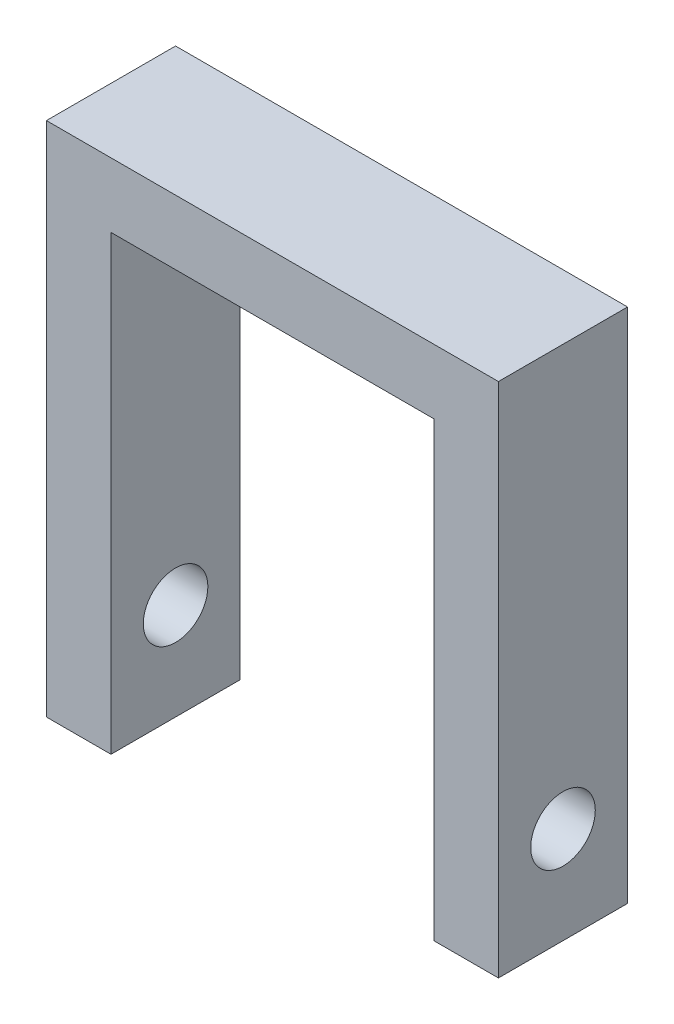
SolidWorks part; units mm, degrees
ref_plane "Front Plane" through (0, 0, 0) normal (0, 0, 1) x (1, 0, 0)
ref_plane "Top Plane" through (0, 0, 0) normal (0, 1, 0) x (1, 0, 0)
ref_plane "Right Plane" through (0, 0, 0) normal (1, 0, 0) x (0, 0, -1)
sketch "Sketch1" plane through (0, 0, 0) normal (0, 0, 1) x (1, 0, 0)
  line L0 (0, 0) -> (0, 70)
  line L1 (0, 70) -> (-50, 70)
  line L2 (-50, 70) -> (-50, 0)
  line L3 (10, 0) -> (10, 80)
  line L4 (10, 80) -> (-60, 80)
  line L5 (-60, 80) -> (-60, 0)
  line L6 (-60, 0) -> (-50, 0)
  line L7 (0, 0) -> (10, 0)
  dimension "D1" = 50
  dimension "D2" = 70
  dimension "D3" = 70
  dimension "D4" = 10
extrude "Boss-Extrude1" add sketch "Sketch1" along normal blind 20
sketch "Sketch2" plane through (0, 0, 0) normal (-1, 0, 0) x (0, 0, 1)
  line L0 (20, 80) -> (20, 0) construction
  line L3 (20, 0) -> (0, 0) construction
  circle A0 centre (10, 15) radius 5
  point P6 (9.1827, 0)
  point P7 (-22.9882, 25.8927)
  dimension "D1" = 10
  dimension "D3" = 15
  dimension "D2" = 10
extrude "Cut-Extrude1" cut sketch "Sketch2" along normal through all both and the other way through all
